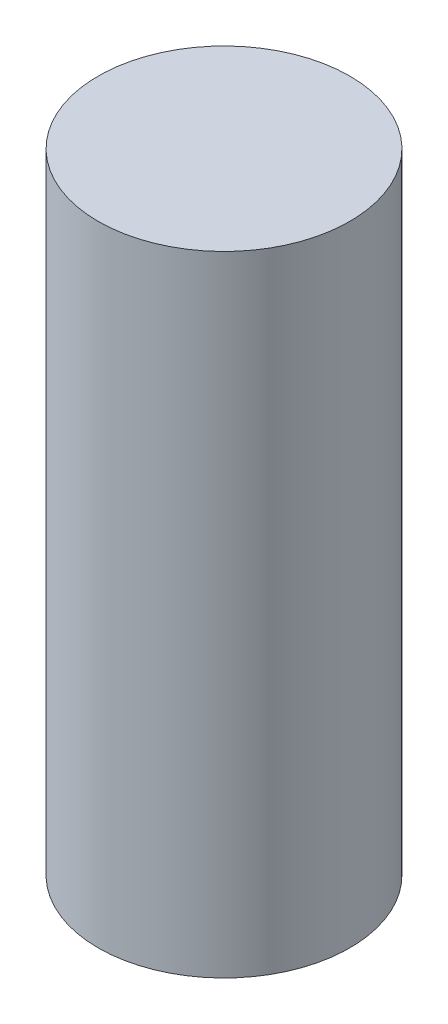
SolidWorks part; units mm, degrees
ref_plane "X-Y Datum" through (0, 0, 0) normal (0, 0, 1) x (1, 0, 0)
ref_plane "X-Z Datum" through (0, 0, 0) normal (0, 1, 0) x (1, 0, 0)
ref_plane "Y-Z Datum" through (0, 0, 0) normal (1, 0, 0) x (0, 0, -1)
sketch "Sketch1" plane through (0, 0, 0) normal (0, 0, 1) x (1, 0, 0)
  line L0 (0, 0) -> (0, 190.5)
  line L1 (0, 0) -> (-38.1, 0)
  line L2 (-38.1, 0) -> (-38.1, 190.5)
  line L3 (-38.1, 190.5) -> (0, 190.5)
  dimension "D1" = 190.5
  dimension "D2" = 38.1
revolve "Revolve1" add sketch "Sketch1" angle 360 about L0
